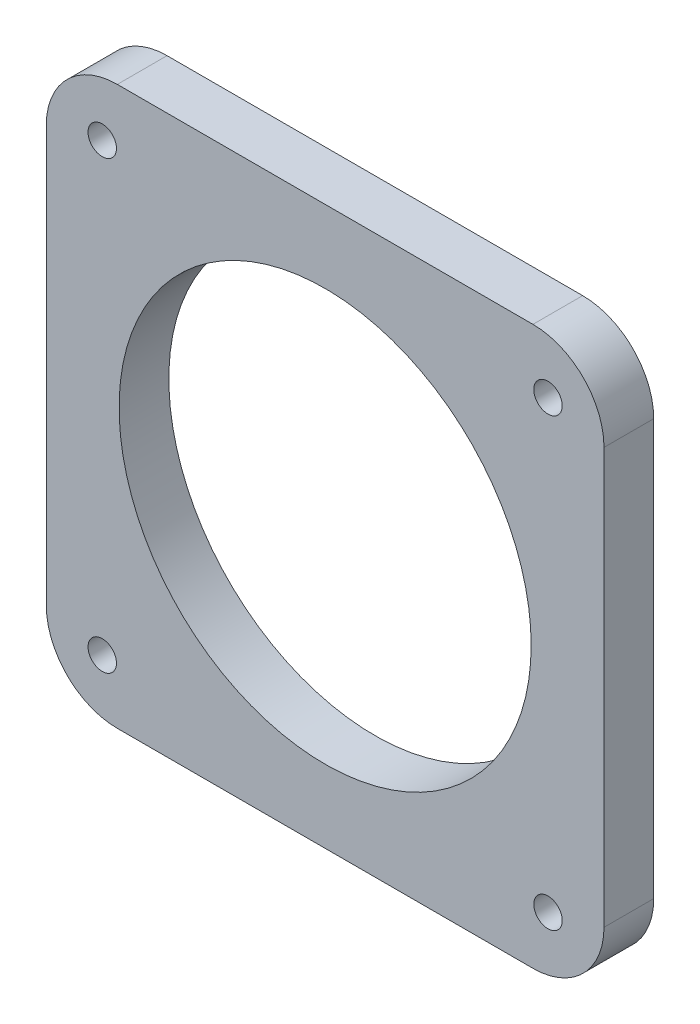
SolidWorks part; units mm, degrees
material "ABS"
ref_plane "Front Plane" through (0, 0, 0) normal (0, 0, 1) x (1, 0, 0)
ref_plane "Top Plane" through (0, 0, 0) normal (0, 1, 0) x (1, 0, 0)
ref_plane "Right Plane" through (0, 0, 0) normal (1, 0, 0) x (0, 0, -1)
sketch "Sketch1" plane through (0, 0, 0) normal (0, 0, 1) x (1, 0, 0)
  line L1 (-39.25, -39.25) -> (39.25, -39.25)
  line L2 (-39.25, -39.25) -> (-39.25, 39.25)
  line L3 (-39.25, 39.25) -> (39.25, 39.25)
  line L4 (39.25, -39.25) -> (39.25, 39.25)
  line L5 (-39.25, -39.25) -> (39.25, 39.25) construction
  line L6 (-39.25, 39.25) -> (39.25, -39.25) construction
  point P0 (0, 0)
  dimension "D1" = 78.5
extrude "Boss-Extrude1" add sketch "Sketch1" along normal mid plane 7
fillet "Fillet1" radius 10 4 edges at (-39.25, -39.25, 0) (39.25, -39.25, 0) (39.25, 39.25, 0) (-39.25, 39.25, 0)
sketch "Sketch2" plane through (0, 0, 3.5) normal (0, 0, 1) x (1, 0, 0)
  line L0 (0, 0) -> (-35355.3391, 35355.3391) construction
  line L1 (0, 0) -> (0, 50000) construction
  line L2 (0, 0) -> (-50000, 0) construction
  circle A0 centre (-31.3713, 31.3713) radius 2
  arc A8 (-29.25, 39.25) -> (-39.25, 29.25) centre (-29.25, 29.25) ccw construction
  circle A9 centre (-31.3713, -31.3713) radius 2
  circle A10 centre (31.3713, 31.3713) radius 2
  circle A11 centre (31.3713, -31.3713) radius 2
  dimension "D2" = 4
  dimension "D3" = 3
  dimension "D1" = 45
extrude "Cut-Extrude1" cut sketch "Sketch2" against normal through all
sketch "Sketch3" plane through (0, 0, 3.5) normal (0, 0, 1) x (1, 0, 0)
  circle A0 centre (0, 0) radius 29
  dimension "D1" = 58
extrude "Cut-Extrude2" cut sketch "Sketch3" against normal through all
